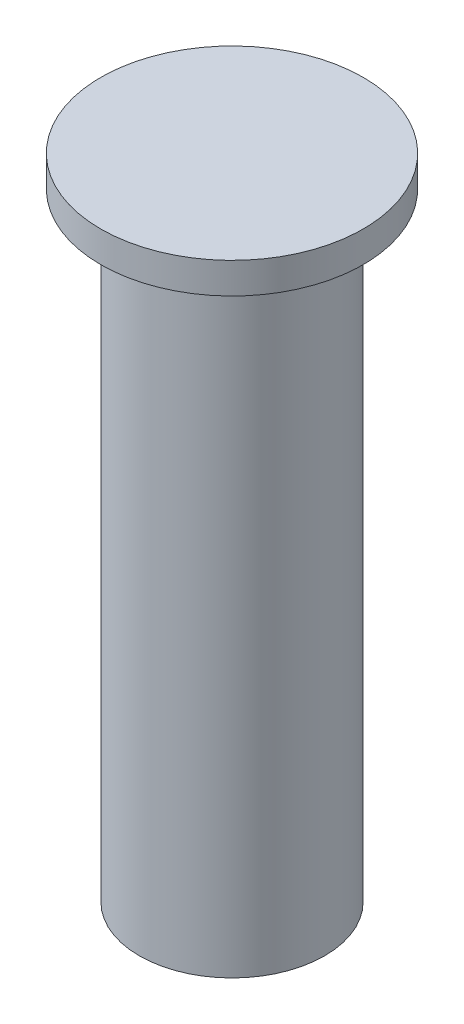
SolidWorks part; units mm, degrees
other "Suspension Pivot Shaft"
ref_plane "Front Plane" through (0, 0, 0) normal (0, 0, 1) x (1, 0, 0)
ref_plane "Top Plane" through (0, 0, 0) normal (0, 1, 0) x (1, 0, 0)
ref_plane "Right Plane" through (0, 0, 0) normal (1, 0, 0) x (0, 0, -1)
sketch3d "Main Profile Sketch datum points"
  point P0 (0, -123, 0)
  point P1 (10, -123, 0)
  point P2 (0, -123, 10)
ref_plane "Main Profile Sketch plane" through (0, -123, 0) normal (0, -1, 0) x (-1, 0, 0)
sketch "Main Profile Sketch" plane through (0, -123, 0) normal (0, -1, 0) x (-1, 0, 0)
  circle A0 centre (56.2917, 0) radius 8.5
extrude "Main Extrusion" add sketch "Main Profile Sketch" along normal blind 2 separate body
sketch3d "Detail Profile 2 Sketch datum points"
  point P0 (0, -125, 0)
  point P1 (10, -125, 0)
  point P2 (0, -125, 10)
ref_plane "Detail Profile 2 Sketch plane" through (0, -125, 0) normal (0, -1, 0) x (-1, 0, 0)
sketch "Detail Profile 2 Sketch" plane through (0, -125, 0) normal (0, -1, 0) x (-1, 0, 0)
  arc A0 (51.3844, -3.4524) -> (50.2917, 0) centre (56.2917, 0) ccw
  arc A1 (50.2917, 0) -> (51.3844, -3.4524) centre (56.2917, 0) ccw
extrude "Detail Extrusion 2" add sketch "Detail Profile 2 Sketch" along normal blind 31.5
sketch3d "Detail Profile 3 Sketch datum points"
  point P0 (0, -156.5, 0)
  point P1 (10, -156.5, 0)
  point P2 (0, -156.5, 10)
ref_plane "Detail Profile 3 Sketch plane" through (0, -156.5, 0) normal (0, -1, 0) x (-1, 0, 0)
sketch "Detail Profile 3 Sketch" plane through (0, -156.5, 0) normal (0, -1, 0) x (-1, 0, 0)
  arc A0 (51.3844, -3.4524) -> (50.2917, 0) centre (56.2917, 0) ccw
  arc A1 (50.2917, 0) -> (51.3844, -3.4524) centre (56.2917, 0) ccw
extrude "Detail Extrusion 3" add sketch "Detail Profile 3 Sketch" along normal blind 0.5
sketch3d "Detail Profile 4 Sketch datum points"
  point P0 (0, -157, 0)
  point P1 (10, -157, 0)
  point P2 (0, -157, 10)
ref_plane "Detail Profile 4 Sketch plane" through (0, -157, 0) normal (0, -1, 0) x (-1, 0, 0)
sketch "Detail Profile 4 Sketch" plane through (0, -157, 0) normal (0, -1, 0) x (-1, 0, 0)
  circle A0 centre (56.2917, 0) radius 6
extrude "Detail Extrusion 4" add sketch "Detail Profile 4 Sketch" along normal blind 8
